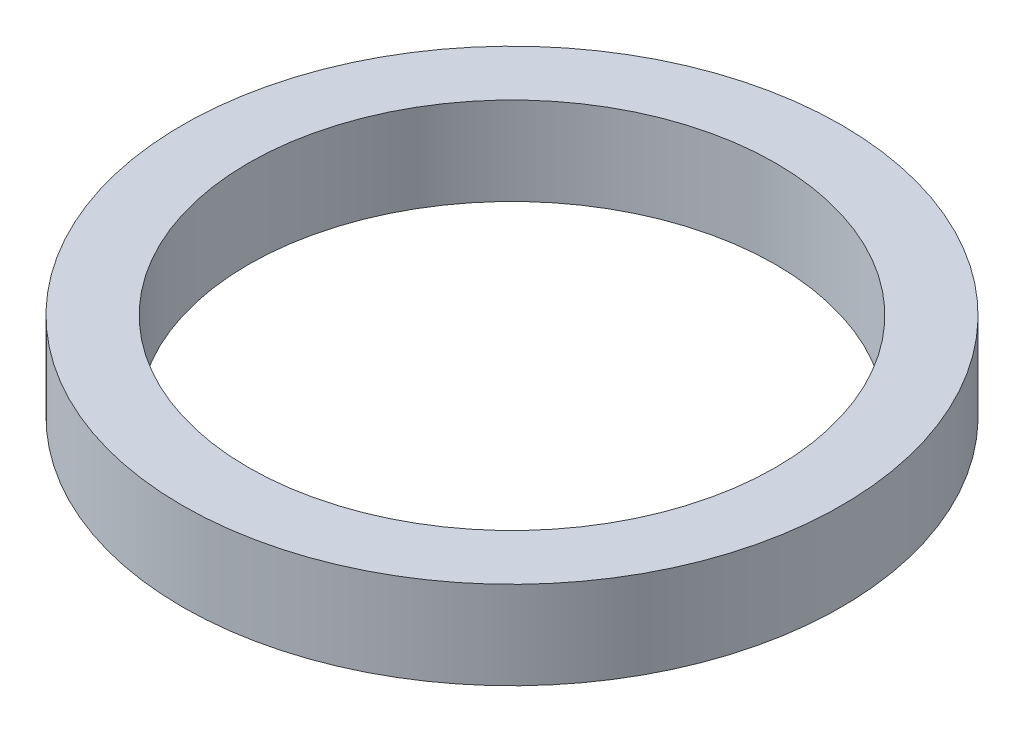
SolidWorks part; units mm, degrees
ref_plane "Front Plane" through (0, 0, 0) normal (0, 0, 1) x (1, 0, 0)
ref_plane "Top Plane" through (0, 0, 0) normal (0, 1, 0) x (1, 0, 0)
ref_plane "Right Plane" through (0, 0, 0) normal (1, 0, 0) x (0, 0, -1)
sketch "Sketch1" plane through (0, 0, 0) normal (0, 1, 0) x (1, 0, 0)
  circle A0 centre (0, 0) radius 6
  circle A1 centre (0, 0) radius 7.5
  dimension "D1" = 12
  dimension "D2" = 15
extrude "Boss-Extrude1" add sketch "Sketch1" along normal blind 2
